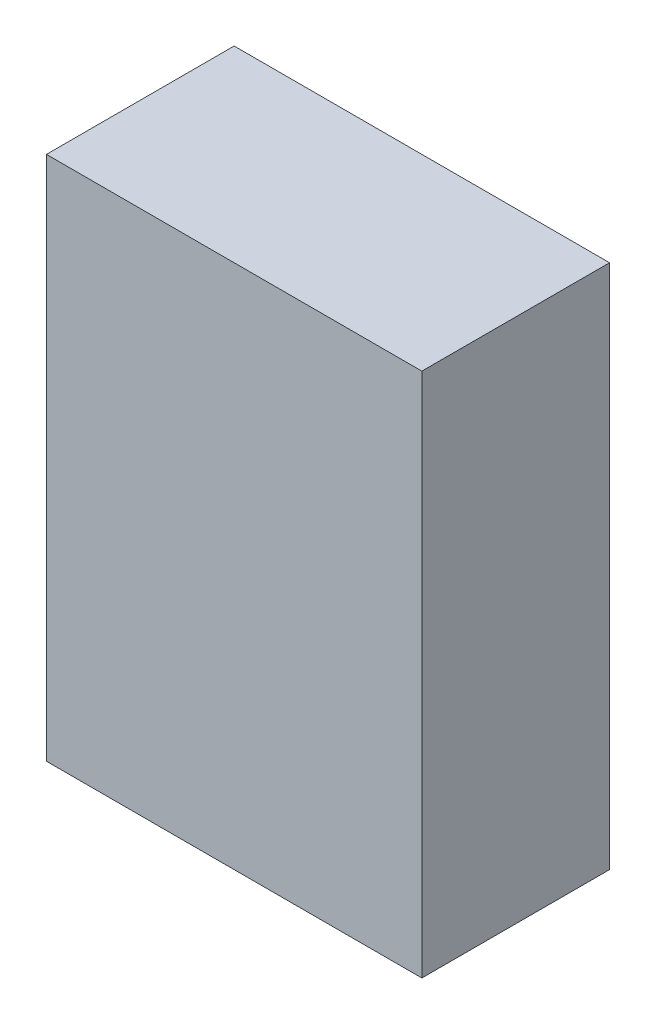
SolidWorks part; units mm, degrees
ref_plane "前基準面" through (0, 0, 0) normal (0, 0, 1) x (1, 0, 0)
ref_plane "上基準面" through (0, 0, 0) normal (0, 1, 0) x (1, 0, 0)
ref_plane "右基準面" through (0, 0, 0) normal (1, 0, 0) x (0, 0, -1)
sketch "草圖1" plane through (0, 0, 0) normal (0, 0, 1) x (1, 0, 0)
  line L1 (0, 0) -> (500, 0)
  line L2 (0, 0) -> (0, 700)
  line L3 (0, 700) -> (500, 700)
  line L4 (500, 0) -> (500, 700)
  dimension "D1" = 500
  dimension "D2" = 700
extrude "填料-伸長1" add sketch "草圖1" along normal blind 250
